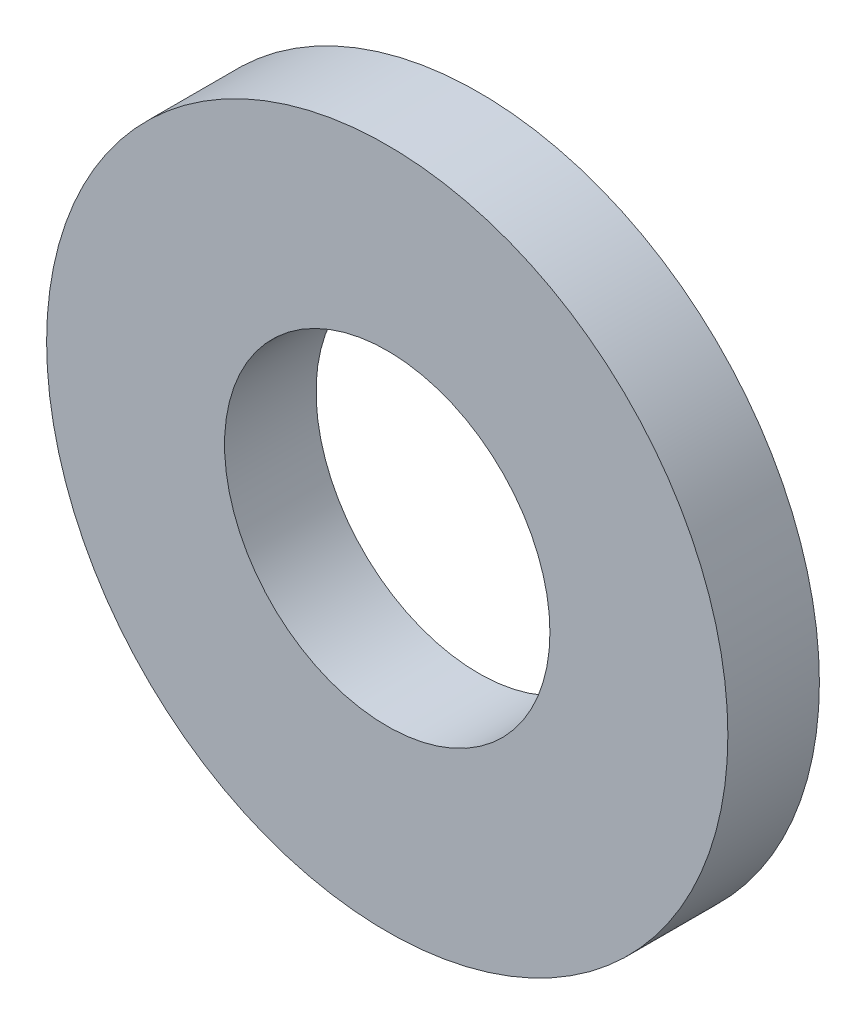
SolidWorks part; units mm, degrees
ref_plane "前视基准面" through (0, 0, 0) normal (0, 0, 1) x (1, 0, 0)
ref_plane "上视基准面" through (0, 0, 0) normal (0, 1, 0) x (1, 0, 0)
ref_plane "右视基准面" through (0, 0, 0) normal (1, 0, 0) x (0, 0, -1)
sketch "草图1" plane through (0, 0, 0) normal (0, 0, 1) x (1, 0, 0)
  circle A0 centre (0, 0) radius 3.35
  circle A1 centre (0, 0) radius 1.6
  dimension "D1" = 3.2
  dimension "D2" = 6.7
extrude "凸台-拉伸1" add sketch "草图1" along normal blind 0.9
